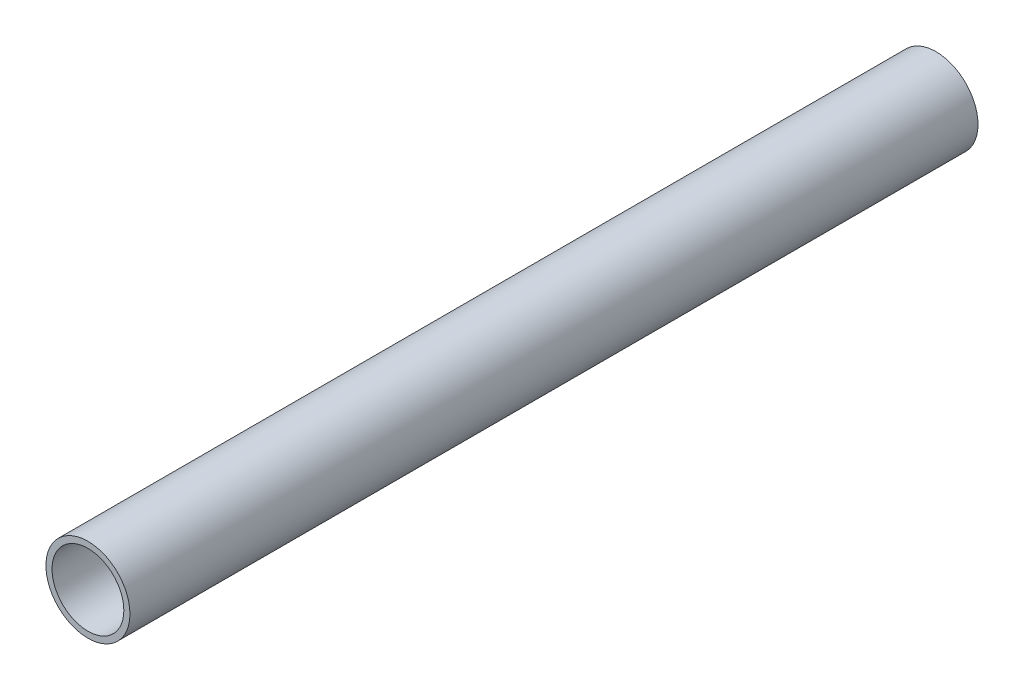
SolidWorks part; units mm, degrees
ref_plane "Alzado" through (0, 0, 0) normal (0, 0, 1) x (1, 0, 0)
ref_plane "Planta" through (0, 0, 0) normal (0, 1, 0) x (1, 0, 0)
ref_plane "Vista lateral" through (0, 0, 0) normal (1, 0, 0) x (0, 0, -1)
other "Tabla de configuración"
sketch "Croquis1" plane through (0, 0, 0) normal (0, 0, 1) x (1, 0, 0)
  circle A0 centre (0, 0) radius 25.4
  circle A1 centre (0, 0) radius 29.72
  dimension "D1" = 59.44
  dimension "D2" = 50.8
extrude "Saliente-Extruir1" add sketch "Croquis1" along normal blind 600
